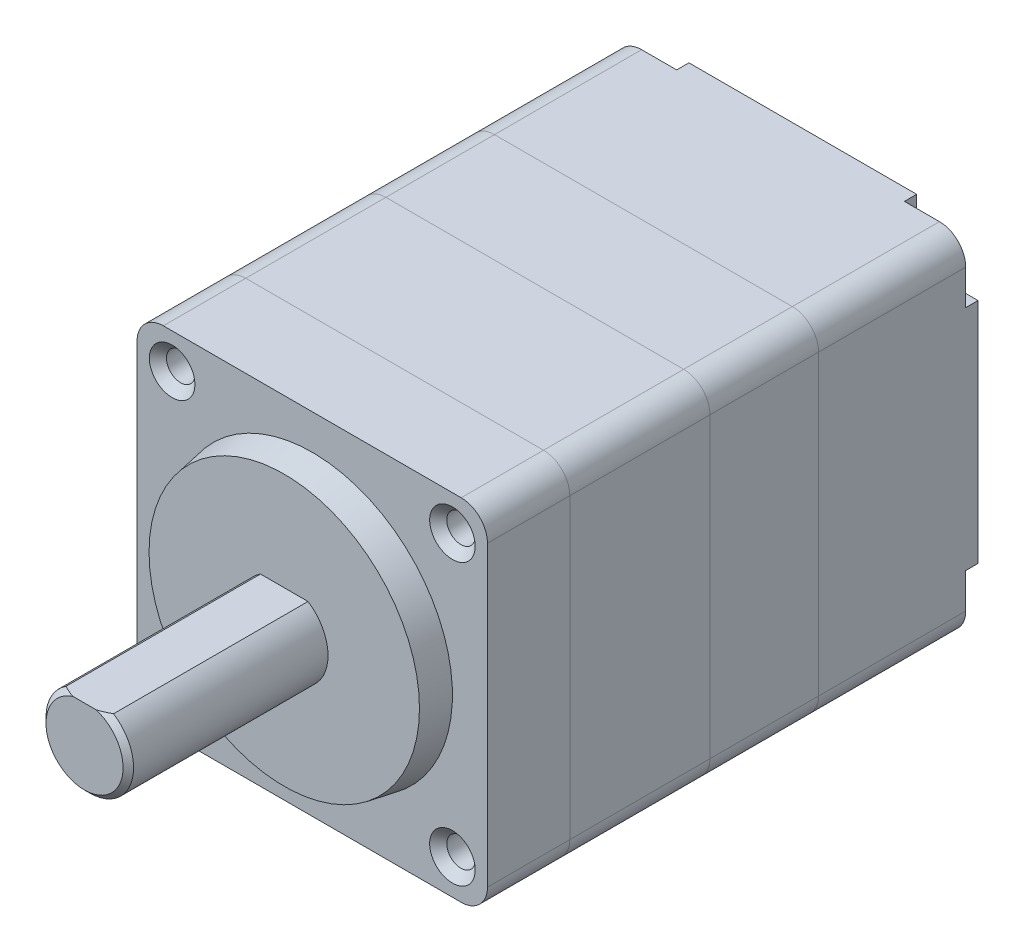
SolidWorks part; units mm, degrees
ref_plane "前视基准面" through (0, 0, 0) normal (0, 0, 1) x (1, 0, 0)
ref_plane "上视基准面" through (0, 0, 0) normal (0, 1, 0) x (1, 0, 0)
ref_plane "右视基准面" through (0, 0, 0) normal (1, 0, 0) x (0, 0, -1)
other "Configuration Table"
sketch "草图1" plane through (0, 0, 0) normal (0, 0, 1) x (1, 0, 0)
  line L1 (-10, 10) -> (10, 10)
  line L2 (-10, 10) -> (-10, -10)
  line L3 (-10, -10) -> (10, -10)
  line L4 (10, 10) -> (10, -10)
  line L5 (-10, 10) -> (10, -10) construction
  line L6 (-10, -10) -> (10, 10) construction
  point P0 (0, 0)
  dimension "D1" = 20
  dimension "D2" = 20
extrude "凸台-拉伸1" add sketch "草图1" along normal blind 9.1
sketch "草图2" plane through (0, 0, 0) normal (0, 0, -1) x (-1, 0, 0)
  line L1 (8, -8) -> (-8, -8) construction
  line L2 (8, -8) -> (8, 8) construction
  line L3 (8, 8) -> (-8, 8) construction
  line L4 (-8, -8) -> (-8, 8) construction
  line L5 (8, -8) -> (-8, 8) construction
  line L6 (8, 8) -> (-8, -8) construction
  circle A0 centre (-8, 8) radius 1
  circle A1 centre (8, 8) radius 1
  circle A2 centre (8, -8) radius 1
  circle A3 centre (-8, -8) radius 1
  point P0 (0, 0)
  dimension "D2" = 2
  dimension "D1" = 16
extrude "切除-拉伸1" cut sketch "草图2" against normal up to next
sketch "草图3" plane through (0, 0, 0) normal (0, 0, -1) x (-1, 0, 0)
  line L1 (-10, 10) -> (-6.5, 10)
  line L2 (-10, 10) -> (-10, 6.5)
  line L3 (-10, 6.5) -> (-6.5, 6.5)
  line L4 (-6.5, 10) -> (-6.5, 6.5)
  line L5 (10, 10) -> (6.5, 10)
  line L6 (10, 10) -> (10, 6.5)
  line L7 (10, 6.5) -> (6.5, 6.5)
  line L8 (6.5, 10) -> (6.5, 6.5)
  line L9 (10, -10) -> (6.5, -10)
  line L10 (10, -10) -> (10, -6.5)
  line L11 (10, -6.5) -> (6.5, -6.5)
  line L12 (6.5, -10) -> (6.5, -6.5)
  line L13 (-10, -10) -> (-6.5, -10)
  line L14 (-10, -10) -> (-10, -6.5)
  line L15 (-10, -6.5) -> (-6.5, -6.5)
  line L16 (-6.5, -10) -> (-6.5, -6.5)
  dimension "D1" = 3.5
extrude "切除-拉伸2" cut sketch "草图3" against normal blind 0.7
fillet "圆角1" radius 1.5 4 edges at (-6.5, -6.5, 0.35) (6.5, -6.5, 0.35) (-6.5, 6.5, 0.35) (6.5, 6.5, 0.35)
sketch "草图4" plane through (0, 0, 9.1) normal (0, 0, 1) x (1, 0, 0)
  line L4 (10, -10) -> (10, 10)
  line L5 (10, 10) -> (-10, 10)
  line L6 (-10, 10) -> (-10, -10)
  line L7 (-10, -10) -> (10, -10)
  line L8 (10, -10) -> (10, 10)
  line L9 (10, 10) -> (-10, 10)
  line L10 (-10, 10) -> (-10, -10)
  line L11 (-10, -10) -> (10, -10)
  dimension "D1" = 0
extrude "凸台-拉伸2" add sketch "草图4" along normal blind 6.2 separate body
sketch "草图5" plane through (0, 0, 15.3) normal (0, 0, 1) x (1, 0, 0)
  line L4 (-10, -10) -> (10, -10)
  line L5 (10, -10) -> (10, 10)
  line L6 (10, 10) -> (-10, 10)
  line L7 (-10, 10) -> (-10, -10)
  line L8 (-10, -10) -> (10, -10)
  line L9 (10, -10) -> (10, 10)
  line L10 (10, 10) -> (-10, 10)
  line L11 (-10, 10) -> (-10, -10)
  dimension "D1" = 0
extrude "凸台-拉伸3" add sketch "草图5" along normal blind 8 separate body
sketch "草图6" plane through (0, 0, 23.3) normal (0, 0, 1) x (1, 0, 0)
  line L1 (8, -8) -> (-8, -8) construction
  line L2 (8, -8) -> (8, 8) construction
  line L3 (8, 8) -> (-8, 8) construction
  line L4 (-8, -8) -> (-8, 8) construction
  line L5 (8, -8) -> (-8, 8) construction
  line L6 (8, 8) -> (-8, -8) construction
  circle A0 centre (-8, 8) radius 1
  circle A1 centre (8, 8) radius 1
  circle A2 centre (-8, -8) radius 1
  circle A3 centre (8, -8) radius 1
  point P0 (0, 0)
  dimension "D2" = 2
  dimension "D1" = 16
extrude "切除-拉伸3" cut sketch "草图6" against normal up to next (8 mm away)
sketch "草图7" plane through (0, 0, 23.3) normal (0, 0, 1) x (1, 0, 0)
  line L4 (-10, 10) -> (-10, -10)
  line L5 (-10, -10) -> (10, -10)
  line L6 (10, -10) -> (10, 10)
  line L7 (10, 10) -> (-10, 10)
  line L8 (-10, 10) -> (-10, -10)
  line L9 (-10, -10) -> (10, -10)
  line L10 (10, -10) -> (10, 10)
  line L11 (10, 10) -> (-10, 10)
  dimension "D1" = 0
extrude "凸台-拉伸4" add sketch "草图7" along normal blind 4.7 separate body
sketch "草图8" plane through (0, 0, 28) normal (0, 0, 1) x (1, 0, 0)
  line L1 (8, -8) -> (-8, -8) construction
  line L2 (8, -8) -> (8, 8) construction
  line L3 (8, 8) -> (-8, 8) construction
  line L4 (-8, -8) -> (-8, 8) construction
  line L5 (8, -8) -> (-8, 8) construction
  line L6 (8, 8) -> (-8, -8) construction
  circle A0 centre (-8, 8) radius 0.8115
  circle A1 centre (8, 8) radius 0.8115
  circle A2 centre (8, -8) radius 0.8115
  circle A3 centre (-8, -8) radius 0.8115
  point P0 (0, 0)
  dimension "D1" = 1.623
  dimension "D2" = 16
extrude "切除-拉伸4" cut sketch "草图8" against normal up to next (4.7 mm away)
fillet "圆角2" radius 1.5 4 edges at (10, -10, 25.65) (-10, -10, 25.65) (-10, 10, 25.65) (10, 10, 25.65)
fillet "圆角3" radius 1.5 4 edges at (-10, -10, 19.3) (10, -10, 19.3) (-10, 10, 19.3) (10, 10, 19.3)
fillet "圆角4" radius 1.5 4 edges at (-10, -10, 12.2) (10, -10, 12.2) (-10, 10, 12.2) (10, 10, 12.2)
fillet "圆角5" radius 1.5 4 edges at (10, -10, 4.9) (-10, -10, 4.9) (-10, 10, 4.9) (10, 10, 4.9)
sketch "草图9" plane through (0, 0, 0) normal (1, 0, 0) x (0, 0, -1)
  line L0 (0, 0) -> (-33.816, 0) construction
  line L1 (-28, 0) -> (-28, 8)
  line L2 (-28, -8.5) -> (-28, 8.5) construction
  line L3 (-28, 8) -> (-29.6, 7.718)
  line L4 (-29.6, 7.718) -> (-29.6, 0)
  line L5 (-29.6, 0) -> (-28, 0)
  dimension "D1" = 16
  dimension "D2" = 15.436
  dimension "D3" = 1.6
revolve "旋转1" add sketch "草图9" angle 360 about L0
sketch "草图10" plane through (0, 0, 29.6) normal (0, 0, 1) x (1, 0, 0)
  line L0 (-1.3565, 2.1) -> (1.3565, 2.1)
  arc A0 (-1.3565, 2.1) -> (1.3565, 2.1) centre (0, 0) ccw
  dimension "D1" = 5
  dimension "D2" = 2.1
extrude "切除-拉伸5" cut sketch "草图10" against normal up to next (1.6 mm away)
sketch "草图11" plane through (0, 0, 28) normal (0, 0, 1) x (1, 0, 0)
  line L0 (1.3565, 2.1) -> (-1.3565, 2.1) construction
  line L1 (1.3565, 2.1) -> (-1.3565, 2.1)
  arc A0 (-1.3565, 2.1) -> (1.3565, 2.1) centre (0, 0) ccw construction
  arc A1 (-1.3565, 2.1) -> (1.3565, 2.1) centre (0, 0) ccw
extrude "凸台-拉伸5" add sketch "草图11" along normal blind 13 separate body
chamfer "倒角1" distance 0.3 angle 45 1 edges at (0, -2.5, 41)
chamfer "倒角2" distance 0.4885 angle 45 4 edges at (8.8115, -8, 28) (-7.1885, -8, 28) (-7.1885, 8, 28) (8.8115, 8, 28)
